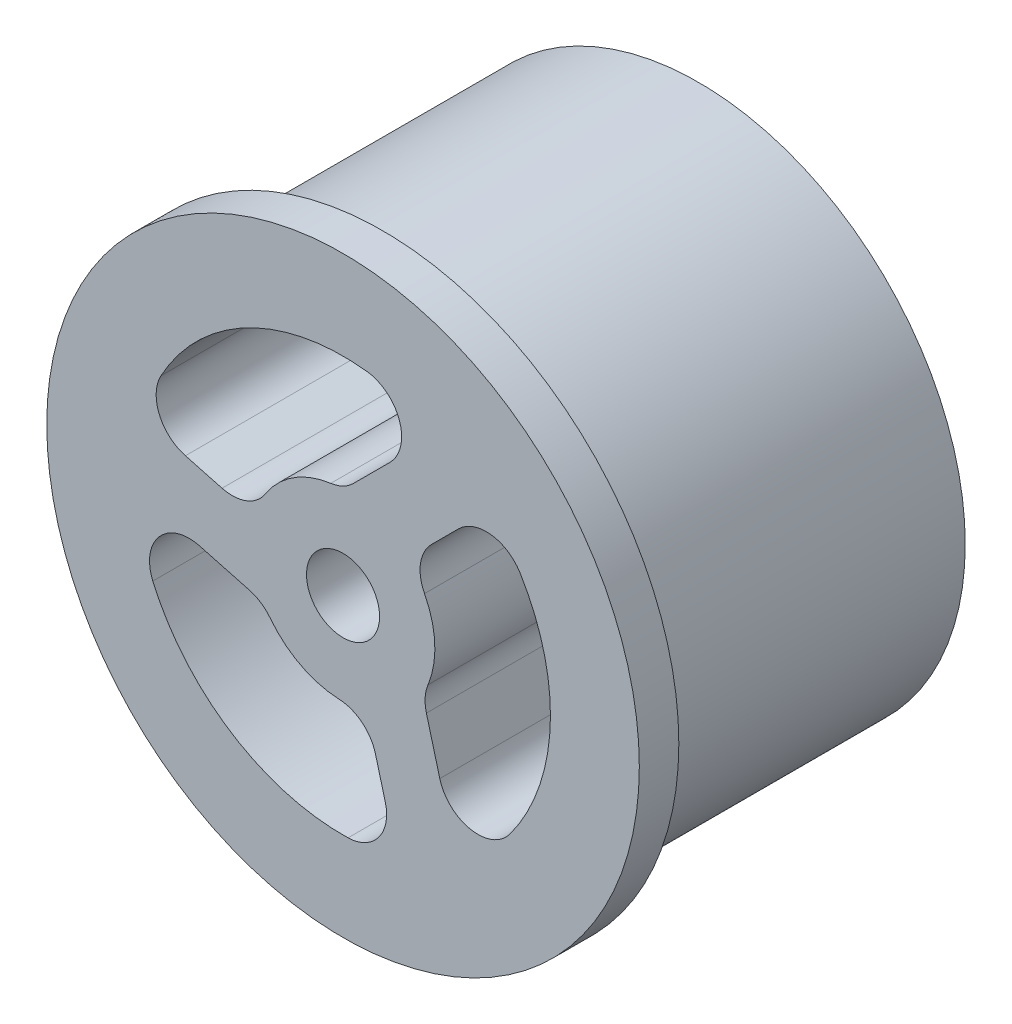
SolidWorks part; units mm, degrees
ref_plane "前视基准面" through (0, 0, 0) normal (0, 0, 1) x (1, 0, 0)
ref_plane "上视基准面" through (0, 0, 0) normal (0, 1, 0) x (1, 0, 0)
ref_plane "右视基准面" through (0, 0, 0) normal (1, 0, 0) x (0, 0, -1)
other "Configuration Table"
sketch "草图1" plane through (0, 0, 0) normal (0, 0, 1) x (1, 0, 0)
  circle A0 centre (0, 0) radius 6.75
  circle A1 centre (0, 0) radius 5.25
  dimension "D1" = 13.5
  dimension "D2" = 1.5
extrude "凸台-拉伸1" add sketch "草图1" along normal blind 9
sketch "草图2" plane through (0, 0, 9) normal (0, 0, 1) x (1, 0, 0)
  line L0 (0, 2.325) -> (2.325, 0)
  line L1 (0, 2.325) -> (3.0691, 5.3941)
  line L2 (2.325, 0) -> (5.3941, 3.0691)
  line L3 (3.0691, 5.3941) -> (5.3941, 3.0691)
  line L4 (2.0135, -1.1625) -> (-1.1625, -2.0135)
  line L5 (2.0135, -1.1625) -> (3.1369, -5.355)
  line L6 (3.1369, -5.355) -> (-0.0391, -6.206)
  line L7 (-1.1625, -2.0135) -> (-0.0391, -6.206)
  line L8 (-2.0135, -1.1625) -> (-1.1625, 2.0135)
  line L9 (-2.0135, -1.1625) -> (-6.206, -0.0391)
  line L10 (-6.206, -0.0391) -> (-5.355, 3.1369)
  line L11 (-1.1625, 2.0135) -> (-5.355, 3.1369)
  line L12 (0, 0) -> (4.2316, 4.2316)
  line L13 (0, 0) -> (-5.7805, 1.5489)
  line L14 (0.4255, -1.588) -> (1.5489, -5.7805)
  circle A0 centre (0, 0) radius 0.925
  circle A1 centre (0, 0) radius 2.325
  point P18 (0, 0)
  circle M6 centre (0, 0) radius 5.25
  dimension "D1" = 1.85
  dimension "D2" = 1.4
  dimension "D3" = 3.288
  dimension "D4" = 3
extrude "凸台-拉伸2" add sketch "草图2" against normal blind 9 contours L8 A1 | L0 A1 L8 L4 A0 | L0 A1 | A1 L2 L1 M6 | L4 A1 | L0 A1 L8 L13 A0 L12 | L12 A1 L0 | L8 A1 L13 | L14 A1 L4 | A1 L14 L5 M6 | A1 L13 L9 M6
fillet "圆角1" radius 1 9 edges at (1.644, 1.644, 4.5) (0, 2.325, 4.5) (-2.2458, 0.6018, 4.5) (-2.0135, -1.1625, 4.5) (0.6018, -2.2458, 4.5) (2.0135, -1.1625, 4.5) (3.7123, 3.7123, 4.5) (1.3588, -5.0711, 4.5) (-5.0711, 1.3588, 4.5)
sketch "草图3" plane through (0, 0, 9) normal (0, 0, 1) x (1, 0, 0)
  circle A0 centre (0, 0) radius 6.75
  circle A1 centre (0, 0) radius 7.5
extrude "凸台-拉伸3" add sketch "草图3" against normal blind 1
fillet "圆角2" radius 1 3 edges at (2.3631, 4.6881, 4.5) (-5.2416, -0.2975, 4.5) (2.8785, -4.3906, 4.5)
